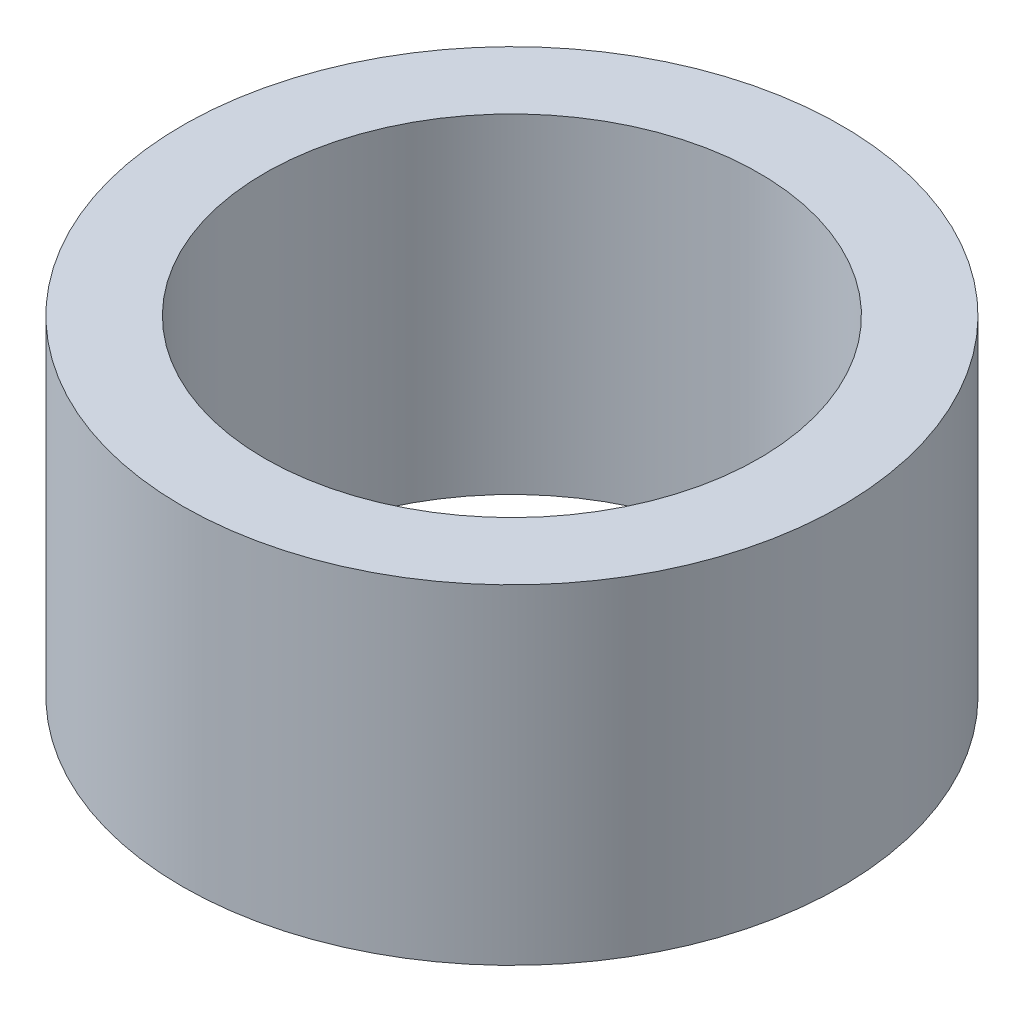
SolidWorks part; units mm, degrees
ref_plane "Front" through (0, 0, 0) normal (0, 0, 1) x (1, 0, 0)
ref_plane "Top" through (0, 0, 0) normal (0, 1, 0) x (1, 0, 0)
ref_plane "Right" through (0, 0, 0) normal (1, 0, 0) x (0, 0, -1)
sketch "Sketch1" plane through (0, 0, 0) normal (0, 1, 0) x (1, 0, 0)
  line L0 (0, 3) -> (0, -2.5)
  line L1 (0, -2.5) -> (-1.6583, -2.5)
  line L2 (-1.6583, -2.5) -> (1.6583, -2.5)
  circle A0 centre (0, 0) radius 3
  circle A1 centre (0, 0) radius 4
extrude "Boss-Extrude1" add sketch "Sketch1" along normal blind 4 contours A1 A0
